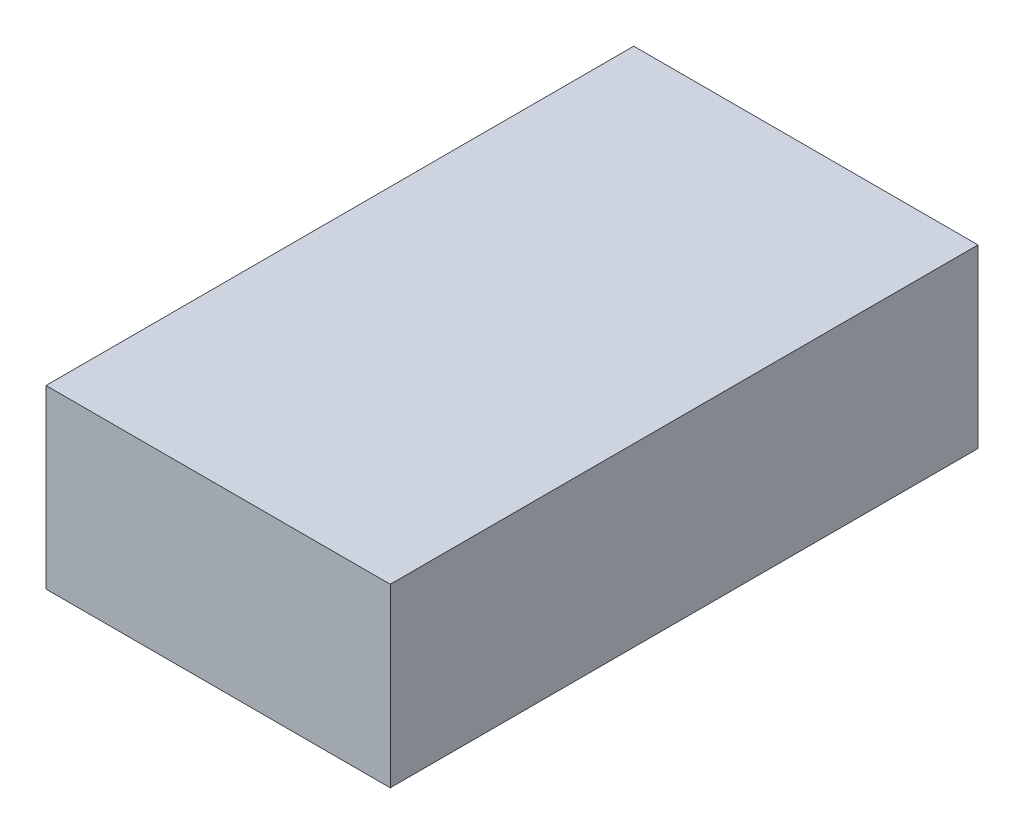
SolidWorks part; units mm, degrees
ref_plane "Front Plane" through (0, 0, 0) normal (0, 0, 1) x (1, 0, 0)
ref_plane "Top Plane" through (0, 0, 0) normal (0, 1, 0) x (1, 0, 0)
ref_plane "Right Plane" through (0, 0, 0) normal (1, 0, 0) x (0, 0, -1)
sketch "Sketch1" plane through (0, 0, 0) normal (0, 0, 1) x (1, 0, 0)
  line L1 (-20.5, 10.5) -> (20.5, 10.5)
  line L2 (-20.5, 10.5) -> (-20.5, -10.5)
  line L3 (-20.5, -10.5) -> (20.5, -10.5)
  line L4 (20.5, 10.5) -> (20.5, -10.5)
  line L5 (-20.5, 10.5) -> (20.5, -10.5) construction
  line L6 (-20.5, -10.5) -> (20.5, 10.5) construction
  point P0 (0, 0)
extrude "Boss-Extrude1" add sketch "Sketch1" along normal blind 70
